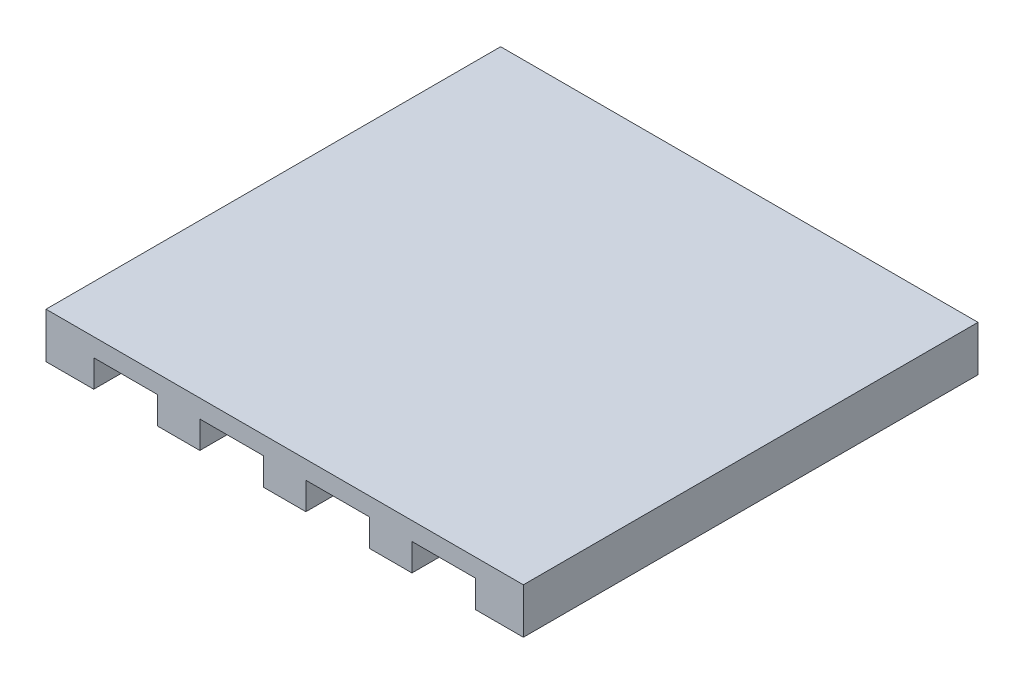
SolidWorks part; units mm, degrees
ref_plane "Front Plane" through (0, 0, 0) normal (0, 0, 1) x (1, 0, 0)
ref_plane "Top Plane" through (0, 0, 0) normal (0, 1, 0) x (1, 0, 0)
ref_plane "Right Plane" through (0, 0, 0) normal (1, 0, 0) x (0, 0, -1)
sketch "Sketch1" plane through (0, 0, 0) normal (0, 1, 0) x (1, 0, 0)
  line L1 (-52.5, -50) -> (52.5, -50)
  line L2 (-52.5, -50) -> (-52.5, 50)
  line L3 (-52.5, 50) -> (52.5, 50)
  line L4 (52.5, -50) -> (52.5, 50)
  line L5 (-52.5, -50) -> (52.5, 50) construction
  line L6 (-52.5, 50) -> (52.5, -50) construction
  point P0 (0, 0)
  dimension "D1" = 105
  dimension "D2" = 100
extrude "Boss-Extrude1" add sketch "Sketch1" along normal blind 10
sketch "Sketch2" plane through (0, 0, 50) normal (0, 0, 1) x (1, 0, 0)
  line L0 (-52.5, 0) -> (52.5, 0) construction
  line L1 (-41.995, 0) -> (-27.995, 0)
  line L2 (-41.995, 0) -> (-41.995, 6)
  line L3 (-41.995, 6) -> (-27.995, 6)
  line L4 (-27.995, 0) -> (-27.995, 6)
  line L5 (-52.5, 10) -> (52.5, 10) construction
  line L6 (-41.995, 3) -> (41.995, 3) construction
  line L9 (-18.665, 0) -> (-4.665, 0)
  line L10 (-18.665, 0) -> (-18.665, 6)
  line L11 (-18.665, 6) -> (-4.665, 6)
  line L12 (-4.665, 0) -> (-4.665, 6)
  line L13 (27.995, 0) -> (41.995, 0)
  line L14 (27.995, 0) -> (27.995, 6)
  line L15 (27.995, 6) -> (41.995, 6)
  line L16 (41.995, 0) -> (41.995, 6)
  line L17 (4.665, 0) -> (18.665, 0)
  line L18 (4.665, 0) -> (4.665, 6)
  line L19 (4.665, 6) -> (18.665, 6)
  line L20 (18.665, 0) -> (18.665, 6)
  point P8 (0, 3)
  point P9 (41.995, 3)
  dimension "D1" = 14
  dimension "D2" = 4
  dimension "D3" = 4
  dimension "D4" = 4
  dimension "D5" = 4
  dimension "D6" = 9.33
  dimension "D7" = 9.33
  dimension "D8" = 9.33
extrude "Cut-Extrude1" cut sketch "Sketch2" against normal blind 35
